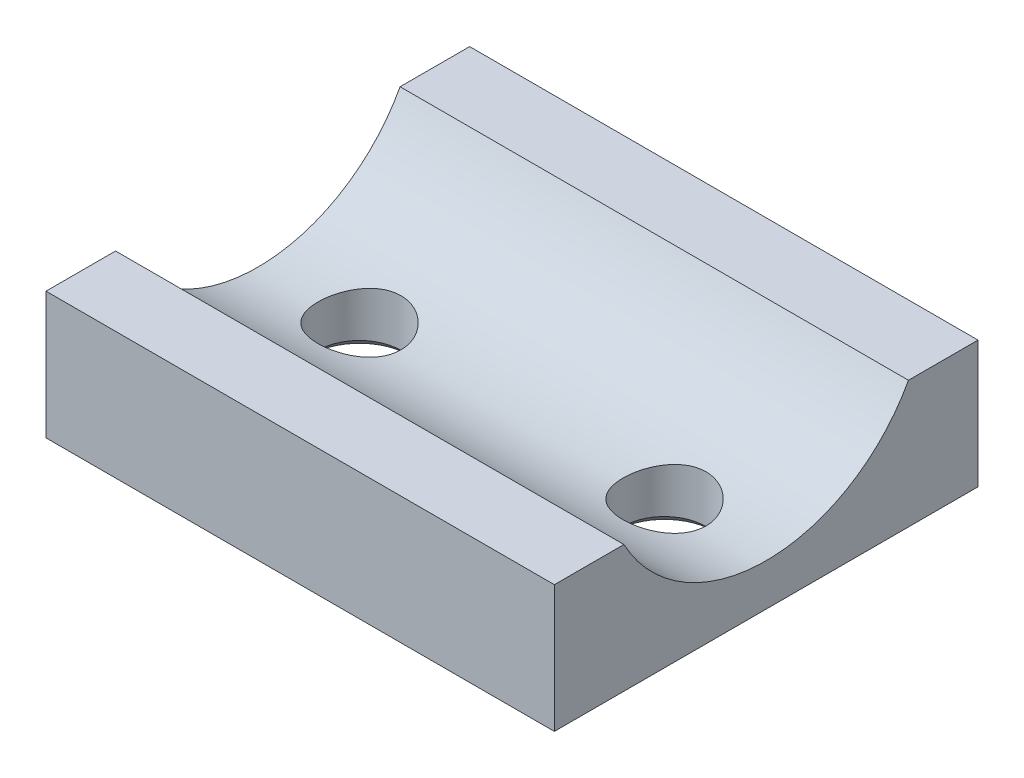
SolidWorks part; units mm, degrees
ref_plane "Front Plane" through (0, 0, 0) normal (0, 0, 1) x (1, 0, 0)
ref_plane "Top Plane" through (0, 0, 0) normal (0, 1, 0) x (1, 0, 0)
ref_plane "Right Plane" through (0, 0, 0) normal (1, 0, 0) x (0, 0, -1)
sketch "Sketch1" plane through (0, 0, 0) normal (1, 0, 0) x (0, 0, -1)
  line L0 (-12.5, -4.5) -> (12.5, -4.5)
  line L1 (12.5, -12.5) -> (-12.5, -12.5)
  line L2 (12.5, -12.5) -> (12.5, 12.5)
  line L3 (12.5, 12.5) -> (-12.5, 12.5)
  line L4 (-12.5, -12.5) -> (-12.5, 12.5)
  line L5 (12.5, -12.5) -> (-12.5, 12.5) construction
  line L6 (12.5, 12.5) -> (-12.5, -12.5) construction
  circle A0 centre (0, 0) radius 9.525
  dimension "D1" = 19.05
  dimension "D2" = 25
  dimension "D3" = 4.5
extrude "Boss-Extrude1" add sketch "Sketch1" along normal mid plane 30 contours A0 L0 L4 L1 L2
sketch "Sketch2" plane through (0, -12.5, 0) normal (0, -1, 0) x (1, 0, 0)
  line L0 (-9, 0) -> (9, 0) construction
  circle A0 centre (9, 0) radius 2.45
  circle A1 centre (-9, 0) radius 2.45
  dimension "D2" = 4.9
  dimension "D1" = 18
extrude "Cut-Extrude1" cut sketch "Sketch2" against normal through all both and the other way through all
sketch "Sketch3" plane through (0, -12.5, 0) normal (0, -1, 0) x (1, 0, 0)
  line L0 (15, 12.5) -> (-15, 12.5) construction
  line L1 (11.5, 12.5) -> (15, 12.5)
  line L2 (15, 12.5) -> (15, 16)
  arc A0 (11.5, 12.5) -> (15, 16) centre (11.5, 16) ccw
  point P3 (0, 0)
  dimension "D1" = 3.5
extrude "Boss-Extrude2" [suppressed] add sketch "Sketch3" against normal up to surface (8 mm away) contours L2 A0 L1
mirror "Mirror1" [suppressed] about plane through (0, 0, 0) normal (0, 0, 1)
chamfer "Chamfer1" distance 0.5 angle 45 6 edges at (0, -12.5, 12.5) (15, -12.5, 0) (0, -12.5, -12.5) (-15, -12.5, 0) (9, -12.5, -2.45) (-9, -12.5, -2.45)
